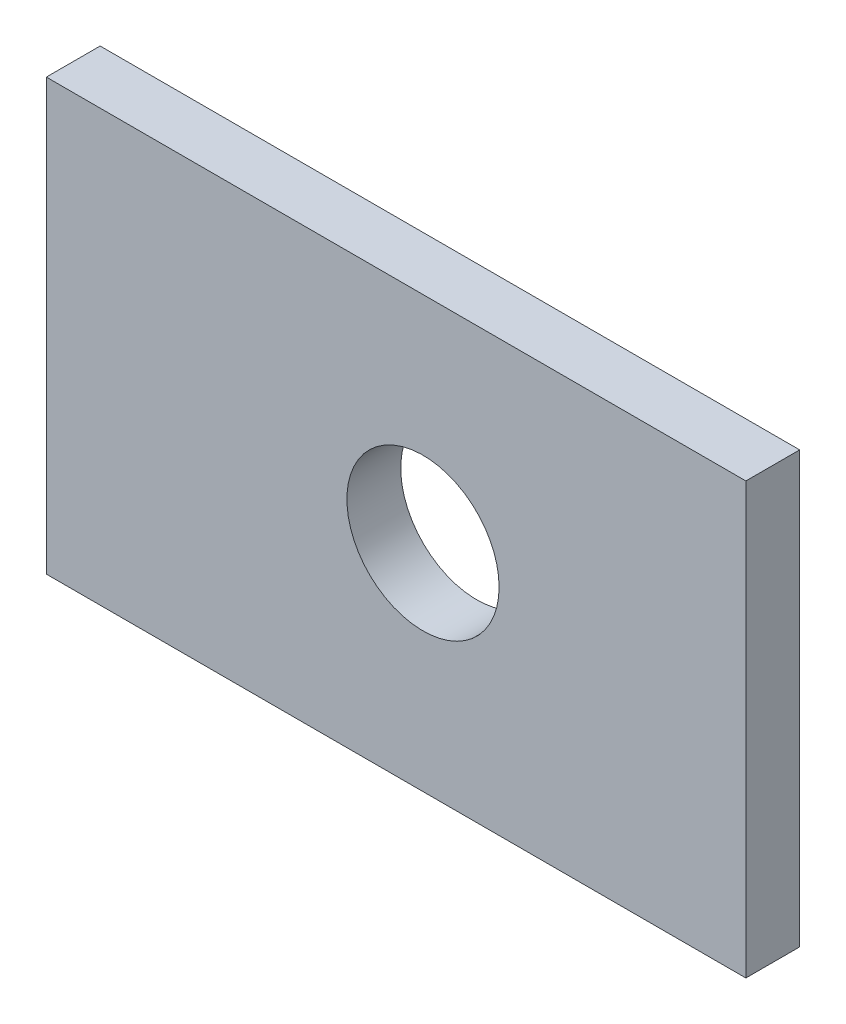
SolidWorks part; units mm, degrees
ref_plane "前视基准面" through (0, 0, 0) normal (0, 0, 1) x (1, 0, 0)
ref_plane "上视基准面" through (0, 0, 0) normal (0, 1, 0) x (1, 0, 0)
ref_plane "右视基准面" through (0, 0, 0) normal (1, 0, 0) x (0, 0, -1)
sketch "草图1" plane through (0, 0, 0) normal (0, 0, 1) x (1, 0, 0)
  line L1 (-50, 30) -> (80, 30)
  line L2 (-50, 30) -> (-50, -50)
  line L3 (-50, -50) -> (80, -50)
  line L4 (80, 30) -> (80, -50)
  circle A0 centre (20, -10) radius 14.1421
extrude "凸台-拉伸1" add sketch "草图1" along normal blind 10
